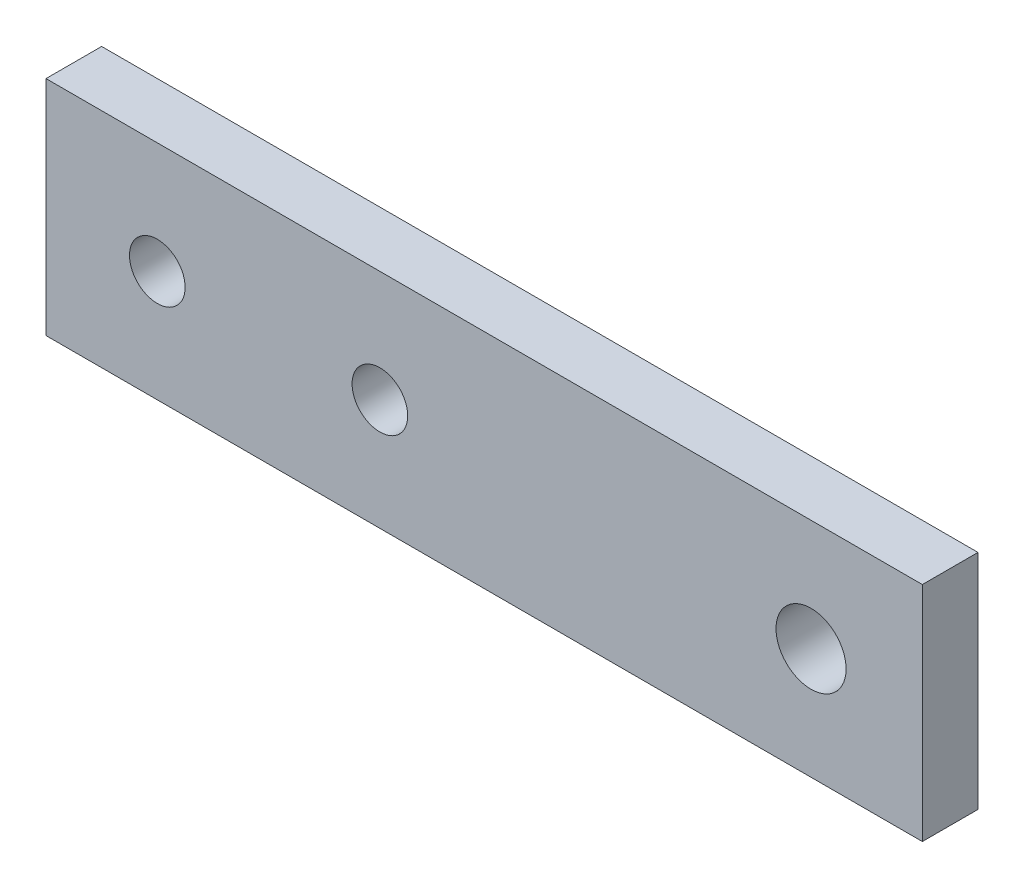
SolidWorks part; units mm, degrees
ref_plane "Front Plane" through (0, 0, 0) normal (0, 0, 1) x (1, 0, 0)
ref_plane "Top Plane" through (0, 0, 0) normal (0, 1, 0) x (1, 0, 0)
ref_plane "Right Plane" through (0, 0, 0) normal (1, 0, 0) x (0, 0, -1)
sketch "Sketch1" plane through (0, 0, 0) normal (1, 0, 0) x (0, 0, -1)
  line L1 (0, 0) -> (6.35, 0)
  line L2 (0, 0) -> (0, 25.4)
  line L3 (0, 25.4) -> (6.35, 25.4)
  line L4 (6.35, 0) -> (6.35, 25.4)
  dimension "D1" = 25.4
  dimension "D2" = 6.35
extrude "Boss-Extrude1" add sketch "Sketch1" along normal blind 100
sketch "Sketch2" plane through (0, 0, 0) normal (0, 0, 1) x (1, 0, 0)
  line L0 (0, 12.7) -> (12.7, 12.7) construction
  line L1 (0, 25.4) -> (0, 0) construction
  line L2 (12.7, 12.7) -> (38.1, 12.7) construction
  line L3 (38.1, 12.7) -> (87.3, 12.7) construction
  line L4 (100, 25.4) -> (100, 0) construction
  circle A0 centre (12.7, 12.7) radius 3.175
  circle A1 centre (38.1, 12.7) radius 3.175
  circle A2 centre (87.3, 12.7) radius 4
  point P9 (100, 12.7)
  dimension "D1" = 6.35
  dimension "D4" = 8
  dimension "D2" = 25.4
  dimension "D3" = 12.7
  dimension "D5" = 12.7
extrude "Cut-Extrude1" cut sketch "Sketch2" against normal through all
